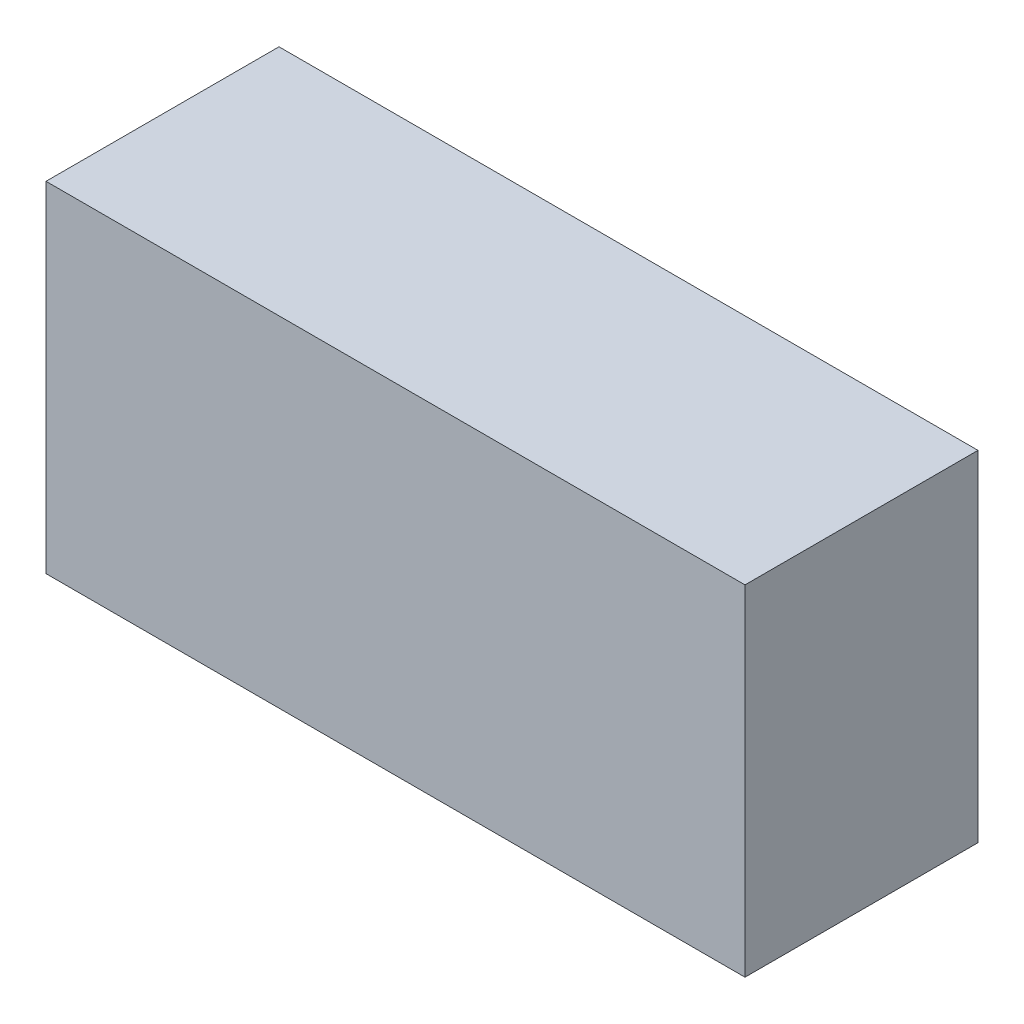
SolidWorks part; units mm, degrees
ref_plane "前视基准面" through (0, 0, 0) normal (0, 0, 1) x (1, 0, 0)
ref_plane "上视基准面" through (0, 0, 0) normal (0, 1, 0) x (1, 0, 0)
ref_plane "右视基准面" through (0, 0, 0) normal (1, 0, 0) x (0, 0, -1)
other "Configuration Table"
sketch "草图1" plane through (0, 0, 0) normal (0, 1, 0) x (1, 0, 0)
  line L1 (0, 0) -> (108, 0)
  line L2 (0, 0) -> (0, 36)
  line L3 (0, 36) -> (108, 36)
  line L4 (108, 0) -> (108, 36)
  dimension "D1" = 108
  dimension "D2" = 36
extrude "凸台-拉伸1" add sketch "草图1" along normal blind 52.5
